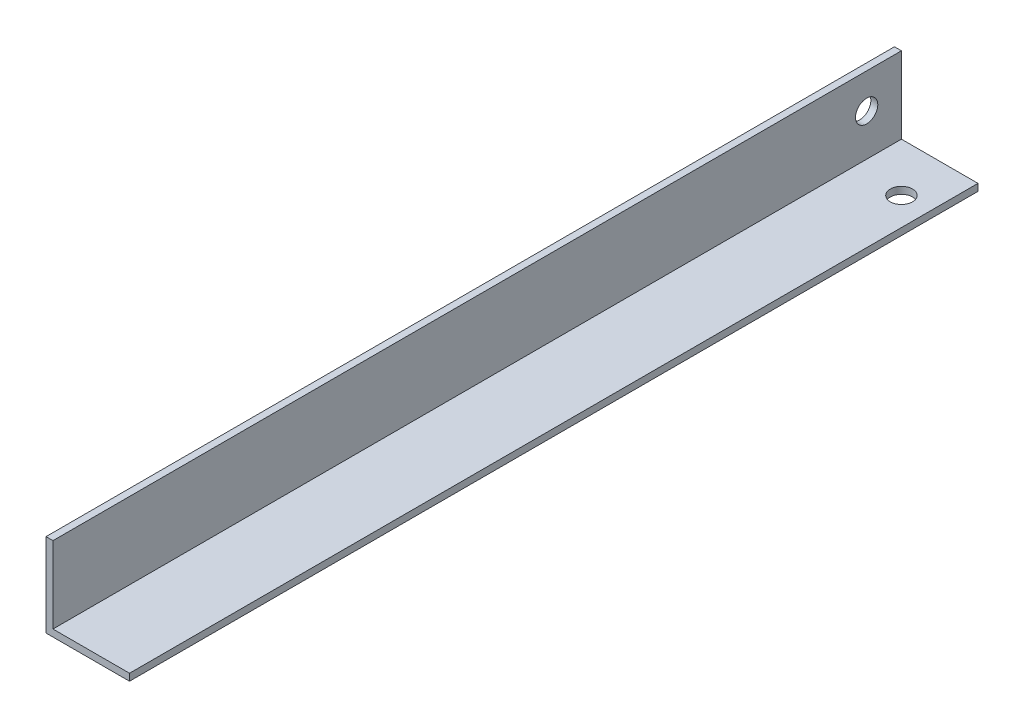
SolidWorks part; units mm, degrees
ref_plane "Front Plane" through (0, 0, 0) normal (0, 0, 1) x (1, 0, 0)
ref_plane "Top Plane" through (0, 0, 0) normal (0, 1, 0) x (1, 0, 0)
ref_plane "Right Plane" through (0, 0, 0) normal (1, 0, 0) x (0, 0, -1)
sketch "Sketch1" plane through (0, 0, 0) normal (0, 0, 1) x (1, 0, 0)
  line L0 (0, 0) -> (0, 30)
  line L1 (0, 30) -> (2.5, 30)
  line L2 (2.5, 30) -> (2.5, 2.5)
  line L3 (2.5, 2.5) -> (30, 2.5)
  line L4 (30, 2.5) -> (30, 0)
  line L5 (30, 0) -> (0, 0)
  dimension "D1" = 2.5
  dimension "D2" = 2.5
  dimension "D3" = 30
  dimension "D4" = 30
extrude "Boss-Extrude1" add sketch "Sketch1" along normal blind 304.8
sketch "Sketch2" plane through (0, 2.5, 0) normal (0, 1, 0) x (1, 0, 0)
  line L1 (30, 0) -> (2.5, 0) construction
  line L2 (30, -304.8) -> (30, 0) construction
  circle A0 centre (20, -17.5) radius 4
  dimension "D2" = 8
  dimension "D3" = 10
  dimension "D4" = 17.5
extrude "Cut-Extrude1" cut sketch "Sketch2" against normal through all
sketch "Sketch3" plane through (2.5, 0, 0) normal (1, 0, 0) x (0, 0, -1)
  line L0 (-152.4, 62.6514) -> (-152.4, -41.7268) construction
  line L1 (0, 2.5) -> (0, 30) construction
  line L2 (-304.8, 30) -> (0, 30) construction
  circle A0 centre (-12.5, 17.5) radius 4
  dimension "D2" = 8
  dimension "D1" = 152.4
  dimension "D3" = 12.5
  dimension "D4" = 12.5
extrude "Cut-Extrude2" cut sketch "Sketch3" against normal through all
